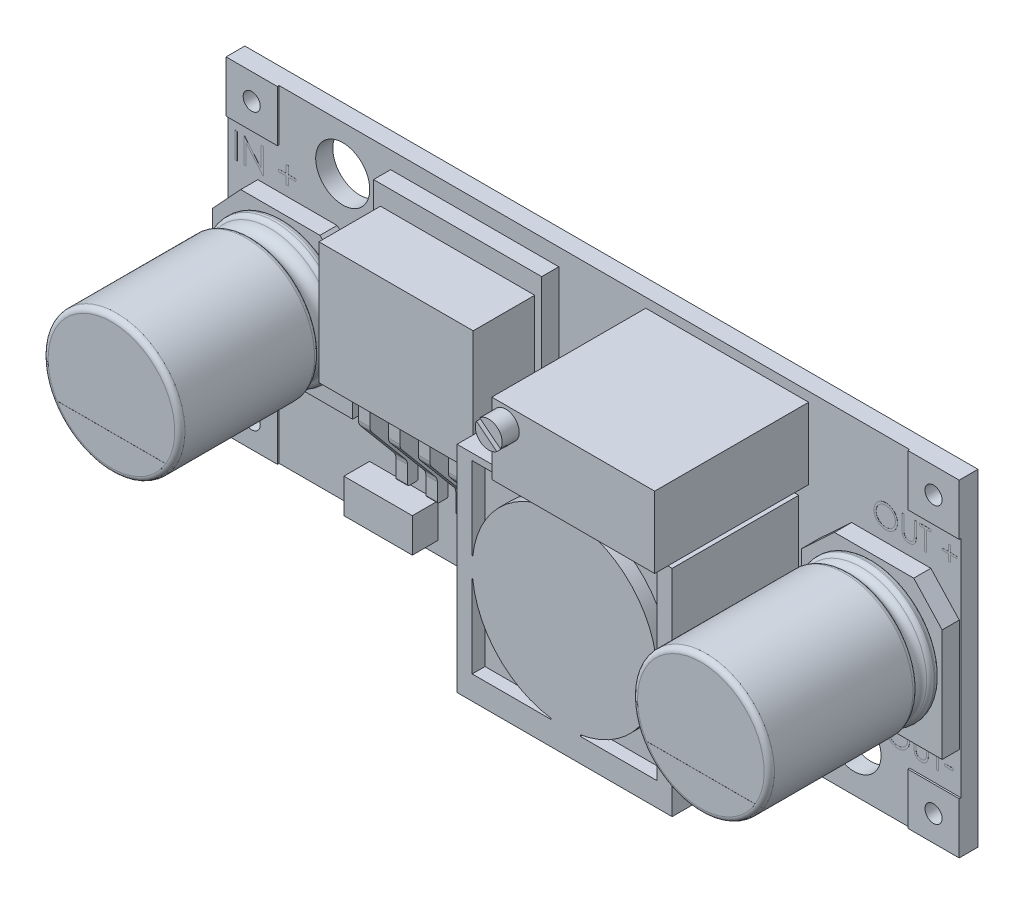
SolidWorks part; units mm, degrees
ref_plane "Front Plane" through (0, 0, 0) normal (0, 0, 1) x (1, 0, 0)
ref_plane "Top Plane" through (0, 0, 0) normal (0, 1, 0) x (1, 0, 0)
ref_plane "Right Plane" through (0, 0, 0) normal (1, 0, 0) x (0, 0, -1)
sketch "Sketch1" plane through (0, 0, 0) normal (0, 0, 1) x (1, 0, 0)
  line L1 (21.4264, -9.5637) -> (-21.4264, -9.5637)
  line L2 (21.4264, -9.5637) -> (21.4264, 9.5637)
  line L3 (21.4264, 9.5637) -> (-21.4264, 9.5637)
  line L4 (-21.4264, -9.5637) -> (-21.4264, 9.5637)
  line L5 (21.4264, -9.5637) -> (-21.4264, 9.5637) construction
  line L6 (21.4264, 9.5637) -> (-21.4264, -9.5637) construction
  circle A0 centre (-14.7064, 6.9537) radius 1.58
  circle A1 centre (15.1764, -6.774) radius 1.58
  point P0 (0, 0)
extrude "Boss-Extrude1" add sketch "Sketch1" along normal blind 1
sketch "Sketch2" plane through (0, 0, 1) normal (0, 0, 1) x (1, 0, 0)
  line L1 (-21.4264, 9.5637) -> (-18.4264, 9.5637)
  line L2 (-21.4264, 9.5637) -> (-21.4264, 6.5637)
  line L3 (-21.4264, 6.5637) -> (-18.4264, 6.5637)
  line L4 (-18.4264, 9.5637) -> (-18.4264, 6.5637)
  line L8 (-18.4264, -9.5637) -> (-18.4264, -6.5637)
  line L9 (-21.4264, -6.5637) -> (-18.4264, -6.5637)
  line L10 (-21.4264, -9.5637) -> (-21.4264, -6.5637)
  line L11 (-21.4264, -9.5637) -> (-18.4264, -9.5637)
  line L12 (21.4264, -9.5637) -> (18.4264, -9.5637)
  line L13 (21.4264, -9.5637) -> (21.4264, -6.5637)
  line L14 (21.4264, -6.5637) -> (18.4264, -6.5637)
  line L15 (18.4264, -9.5637) -> (18.4264, -6.5637)
  line L16 (18.4264, 9.5637) -> (18.4264, 6.5637)
  line L17 (21.4264, 6.5637) -> (18.4264, 6.5637)
  line L18 (21.4264, 9.5637) -> (21.4264, 6.5637)
  line L19 (21.4264, 9.5637) -> (18.4264, 9.5637)
extrude "Boss-Extrude2" add sketch "Sketch2" along normal blind 0.1
sketch "Sketch3" plane through (0, 0, 1.1) normal (0, 0, 1) x (1, 0, 0)
  circle A0 centre (-19.9264, 8.0637) radius 0.5
  circle A1 centre (-19.9264, -8.0637) radius 0.5
  circle A2 centre (19.9264, -8.0637) radius 0.5
  circle A3 centre (19.9264, 8.0637) radius 0.5
extrude "Cut-Extrude1" cut sketch "Sketch3" against normal blind 5
sketch "Sketch4" plane through (0, 0, 1) normal (0, 0, 1) x (1, 0, 0)
  line L5 (-21.3314, 2.3832) -> (-19.6699, 4.175)
  line L6 (-19.6699, 4.175) -> (-15.0378, 4.175)
  line L7 (-21.3314, -4.175) -> (-13.1214, -4.175)
  line L8 (-21.3314, -4.175) -> (-21.3314, 2.3832)
  line L9 (-19.6699, 4.175) -> (-15.0378, 4.175)
  line L10 (-13.1214, -4.175) -> (-13.1214, 2.398)
  line L11 (-21.3314, -4.175) -> (-14.0353, 3.2455) construction
  line L12 (-20.4763, 3.3054) -> (-13.1214, -4.175) construction
  line L13 (-15.0378, 4.175) -> (-13.1214, 2.398)
  line L14 (20.4763, 3.3054) -> (13.1214, -4.175) construction
  line L15 (21.3314, -4.175) -> (14.0353, 3.2455) construction
  line L16 (15.0378, 4.175) -> (13.1214, 2.398)
  line L17 (13.1214, -4.175) -> (13.1214, 2.398)
  line L18 (19.6699, 4.175) -> (15.0378, 4.175)
  line L19 (21.3314, -4.175) -> (21.3314, 2.3832)
  line L20 (21.3314, -4.175) -> (13.1214, -4.175)
  line L21 (19.6699, 4.175) -> (15.0378, 4.175)
  line L22 (21.3314, 2.3832) -> (19.6699, 4.175)
  point P13 (-17.2264, 0)
  point P28 (17.2264, 0)
extrude "Boss-Extrude3" add sketch "Sketch4" along normal blind 1 contours L13 L6 L5 L8 L7 L10 | L19 L22 L18 L16 L17 L20
sketch "Sketch5" plane through (0, 0, 2) normal (0, 0, 1) x (1, 0, 0)
  circle A0 centre (-17.2264, 0) radius 4.105
  circle A1 centre (17.2264, 0) radius 4.105
sketch "Sketch6" plane through (0, 0, 1) normal (0, 0, 1) x (1, 0, 0)
  line L5 (-11.9064, 8.5637) -> (-2.0764, 8.5637)
  line L6 (-11.9064, 8.5637) -> (-11.9064, -0.1863)
  line L7 (-11.9064, -0.1863) -> (-2.0764, -0.1863)
  line L8 (-2.0764, 8.5637) -> (-2.0764, -0.1863)
extrude "Boss-Extrude5" add sketch "Sketch6" along normal blind 4.6
sketch "Sketch7" plane through (0, 0, 5.6) normal (0, 0, 1) x (1, 0, 0)
  line L3 (-11.4988, 7.4182) -> (-2.4839, 7.4182)
  line L4 (-11.4988, 0.2879) -> (-2.4839, 0.2879)
  line L5 (-11.4988, 0.2879) -> (-11.4988, 7.4182)
  line L7 (-2.4839, 0.2879) -> (-2.4839, 7.4182)
  line L11 (-11.9064, -0.1863) -> (-2.0764, -0.1863)
  line L12 (-11.9064, -0.1863) -> (-11.9064, 8.5637)
  line L13 (-11.9064, 8.5637) -> (-2.0764, 8.5637)
  line L14 (-2.0764, -0.1863) -> (-2.0764, 8.5637)
  point P6 (-6.9914, 4.1887)
  point P13 (-6.9914, 4.1887)
extrude "Cut-Extrude2" cut sketch "Sketch7" against normal blind 3.6
sketch "Sketch8" plane through (0, 0.2879, 0) normal (0, -1, 0) x (-1, 0, 0)
  line L0 (9.1927, -4.7708) -> (9.1927, -1.0208)
  line L1 (10.9427, -4.7708) -> (10.2713, -4.7708)
  line L2 (10.9427, -4.7708) -> (10.9427, -1.0208)
  line L3 (10.9427, -1.0208) -> (10.2713, -1.0208)
  line L4 (10.2713, -4.7708) -> (10.2713, -1.0208)
  line L5 (9.1927, -4.7708) -> (8.5213, -4.7708)
  line L6 (8.5213, -4.7708) -> (8.5213, -1.0208)
  line L7 (9.1927, -1.0208) -> (8.5213, -1.0208)
  line L8 (7.4427, -4.7708) -> (7.4427, -1.0208)
  line L9 (7.4427, -4.7708) -> (6.7713, -4.7708)
  line L10 (6.7713, -4.7708) -> (6.7713, -1.0208)
  line L11 (7.4427, -1.0208) -> (6.7713, -1.0208)
  line L12 (5.6927, -4.7708) -> (5.6927, -1.0208)
  line L13 (5.6927, -4.7708) -> (5.0213, -4.7708)
  line L14 (5.0213, -4.7708) -> (5.0213, -1.0208)
  line L15 (5.6927, -1.0208) -> (5.0213, -1.0208)
  line L16 (3.9427, -4.7708) -> (3.9427, -1.0208)
  line L17 (3.9427, -4.7708) -> (3.2713, -4.7708)
  line L18 (3.2713, -4.7708) -> (3.2713, -1.0208)
  line L19 (3.9427, -1.0208) -> (3.2713, -1.0208)
  dimension "D1" = 5
extrude "Boss-Extrude6" add sketch "Sketch8" along normal blind 8
sketch "Sketch10" plane through (0, 0, 1) normal (0, 0, 1) x (1, 0, 0)
  line L5 (11.9464, -8.5637) -> (-0.6236, -8.5637)
  line L6 (11.9464, -8.5637) -> (11.9464, 4.0063)
  line L7 (11.9464, 4.0063) -> (-0.6236, 4.0063)
  line L8 (-0.6236, -8.5637) -> (-0.6236, 4.0063)
extrude "Boss-Extrude7" add sketch "Sketch10" along normal blind 7.4
sketch "Sketch11" plane through (0, 0, 8.4) normal (0, 0, 1) x (1, 0, 0)
  line L0 (0.2614, -1.1682) -> (0.2922, -1.2029)
  line L3 (0.2614, -2.3394) -> (0.2922, -2.3545)
  line L4 (0.2614, -7.1787) -> (4.8799, -7.1787)
  line L5 (0.2614, -7.1787) -> (0.2614, -2.3394)
  line L6 (0.2614, 3.6213) -> (4.9528, 3.6213)
  line L7 (11.0614, -7.1787) -> (11.0614, -2.7691)
  line L8 (0.2614, -7.1787) -> (11.0614, 3.6213) construction
  line L9 (0.2614, 3.6213) -> (11.0614, -7.1787) construction
  line L10 (4.9528, 3.6213) -> (4.9528, 3.5746)
  line L11 (6.2806, 3.6213) -> (6.2806, 3.5857)
  line L12 (10.9698, -0.7882) -> (11.0614, -0.7882)
  line L13 (10.9698, -2.7691) -> (11.0614, -2.7691)
  line L14 (4.8799, -7.1787) -> (4.8799, -7.1218)
  line L15 (6.582, -7.1787) -> (6.582, -7.0996)
  line L16 (6.582, -7.1787) -> (11.0614, -7.1787)
  line L17 (0.2614, -1.1682) -> (0.2614, 3.6213)
  line L18 (6.2806, 3.6213) -> (11.0614, 3.6213)
  line L19 (11.0614, -0.7882) -> (11.0614, 3.6213)
  arc A0 (6.582, -7.0996) -> (10.9698, -2.7691) centre (5.6614, -1.7787) ccw
  arc A1 (0.2922, -2.3545) -> (4.8799, -7.1218) centre (5.6614, -1.7787) ccw
  arc A2 (4.9528, 3.5746) -> (0.2922, -1.2029) centre (5.6614, -1.7787) ccw
  arc A3 (10.9698, -0.7882) -> (6.2806, 3.5857) centre (5.6614, -1.7787) ccw
  point P6 (5.6614, -1.7787)
extrude "Cut-Extrude7" cut sketch "Sketch11" against normal blind 0.75
sketch "Sketch13" plane through (0, 0, 1) normal (0, 0, 1) x (1, 0, 0)
  line L1 (12.527, 4.8371) -> (3.007, 4.8371)
  line L2 (12.527, 4.8371) -> (12.527, 9.0071)
  line L3 (12.527, 9.0071) -> (3.007, 9.0071)
  line L4 (3.007, 4.8371) -> (3.007, 9.0071)
extrude "Boss-Extrude8" add sketch "Sketch13" along normal blind 9
sketch "Sketch14" plane through (0, 0, 10) normal (0, 0, 1) x (1, 0, 0)
  circle A0 centre (3.8265, 8.0224) radius 0.7858
extrude "Boss-Extrude9" add sketch "Sketch14" along normal blind 1
sketch "Sketch16" plane through (0, 0, 11) normal (0, 0, 1) x (1, 0, 0)
  line L0 (3.1748, 8.7082) -> (4.6558, 7.5307)
  line L1 (4.6558, 7.5307) -> (4.4523, 7.2747)
  line L2 (4.4523, 7.2747) -> (2.9713, 8.4522)
  line L3 (2.9713, 8.4522) -> (3.1748, 8.7082)
extrude "Cut-Extrude8" cut sketch "Sketch16" against normal blind 0.4
sketch "Sketch17" plane through (0, 0, 0) normal (0, 1, 0) x (1, 0, 0)
  line L0 (-17.2264, -2) -> (-17.2264, -12)
  line L1 (-21.3314, -2) -> (-13.1214, -2) construction
  line L2 (-17.2264, -12) -> (-20.9264, -12)
  line L3 (-21.2264, -11.7) -> (-21.2264, -4.1269)
  line L4 (-20.9264, -2) -> (-17.2264, -2)
  line L5 (-21.2264, -2.4494) -> (-21.2264, -2.3)
  arc A0 (-21.0274, -2.7319) -> (-21.0274, -3.8444) centre (-21.2264, -3.2881) cw
  arc A1 (-20.9264, -2) -> (-21.2264, -2.3) centre (-20.9264, -2.3) ccw
  arc A2 (-21.2264, -2.4494) -> (-21.0274, -2.7319) centre (-20.9264, -2.4494) ccw
  arc A3 (-21.0274, -3.8444) -> (-21.2264, -4.1269) centre (-20.9264, -4.1269) ccw
  arc A4 (-21.2264, -11.7) -> (-20.9264, -12) centre (-20.9264, -11.7) ccw
  point P12 (-21.2264, -2)
  point P15 (-21.2264, -2.6973)
  point P20 (-21.2264, -12)
  dimension "D3" = 0.3
  dimension "D4" = 0.3
  dimension "D5" = 0.3
  dimension "D6" = 0.3
  dimension "D1" = 10
  dimension "D2" = 4
revolve "Revolve1" add sketch "Sketch17" angle 360 about L0
sketch "Sketch18" plane through (0, 0, 0) normal (0, 1, 0) x (1, 0, 0)
  line L0 (17.2264, -2) -> (17.2264, -12)
  line L1 (21.3314, -2) -> (13.1214, -2) construction
  line L2 (17.2264, -12) -> (20.9264, -12)
  line L3 (21.2264, -11.7) -> (21.2264, -3.6026)
  line L4 (20.9264, -2) -> (17.2264, -2)
  line L5 (21.2264, -2.364) -> (21.2264, -2.3)
  arc A0 (21.0572, -2.634) -> (21.0572, -3.3326) centre (21.2264, -2.9833) ccw
  arc A1 (21.2264, -11.7) -> (20.9264, -12) centre (20.9264, -11.7) cw
  arc A2 (21.0572, -3.3326) -> (21.2264, -3.6026) centre (20.9264, -3.6026) cw
  arc A3 (21.0572, -2.634) -> (21.2264, -2.364) centre (20.9264, -2.364) ccw
  arc A4 (20.9264, -2) -> (21.2264, -2.3) centre (20.9264, -2.3) cw
  point P11 (21.2264, -12)
  point P16 (21.2264, -2.5952)
  point P19 (21.2264, -2)
  dimension "D3" = 0.3
  dimension "D1" = 10
  dimension "D2" = 4
revolve "Revolve2" add sketch "Sketch18" angle 360 about L0
sketch "Sketch20" plane through (-10.9427, 0, 0) normal (-1, 0, 0) x (0, 0, 1)
  line L0 (3.8444, 0.2896) -> (3.8444, -2.2336)
  line L1 (3.8444, 3.801) -> (3.8444, -3.801) construction
  line L2 (3.7275, -2.5549) -> (1.7713, -4.8877)
  line L3 (1.6544, -5.209) -> (1.6544, -6.2296)
  line L4 (1.5544, -6.3296) -> (1.1197, -6.3296)
  line L5 (1.0208, -7.7121) -> (1.0208, -0.1863) construction
  line L6 (1.0197, -6.2308) -> (1.0208, -4.4558)
  line L8 (1.1189, -4.3365) -> (2.9146, -2.1951)
  line L9 (8.1377, -10.4913) -> (1.0208, -10.4913)
  line L10 (3.0315, 0.2896) -> (3.0315, -1.8738)
  line L11 (1.0208, -4.4558) -> (1.1189, -4.3365)
  line L12 (3.0315, 0.2896) -> (1, 0.2896)
  line L13 (8.1377, -10.4913) -> (8.1377, 0.2896)
  line L14 (8.1377, 0.2896) -> (3.8444, 0.2896)
  line L15 (1, 6.5637) -> (1, -6.5637) construction
  line L16 (1, 0.2896) -> (1.0208, -10.4913)
  arc A1 (1.6544, -5.209) -> (1.7713, -4.8877) centre (2.1544, -5.209) cw
  arc A2 (2.9146, -2.1951) -> (3.0315, -1.8738) centre (2.5315, -1.8738) ccw
  arc A3 (3.8444, -2.2336) -> (3.7275, -2.5549) centre (3.3444, -2.2336) cw
  arc A4 (1.1197, -6.3296) -> (1.0197, -6.2308) centre (1.1197, -6.2296) cw
  arc A5 (1.5544, -6.3296) -> (1.6544, -6.2296) centre (1.5544, -6.2296) ccw
  point P23 (3.8444, -2.4155)
  point P26 (1.0208, -6.3296)
  dimension "D2" = 0.1
extrude "Cut-Extrude10" cut sketch "Sketch20" against normal blind 9
sketch "Sketch21" plane through (-10.9427, 0, 0) normal (1, 0, 0) x (0, 0, -1)
  line L0 (-2, -0.1841) -> (-1, -0.1841)
  line L1 (-2, -4.175) -> (-2, 2.3832) construction
  line L2 (-1, -4.175) -> (-1, 2.3832) construction
  line L3 (-2, -0.1841) -> (-2, 0.2879)
  line L4 (-1, -0.1841) -> (-1, 0.2879)
  line L5 (-1, 0.2879) -> (-2, 0.2879)
extrude "Boss-Extrude11" add sketch "Sketch21" along normal blind 8.8665
sketch "Sketch24" plane through (0, 0, 0) normal (0, 0, -1) x (-1, 0, 0)
  text T0 "<b>DC to DC</b>"
extrude "Boss-Extrude15" add sketch "Sketch24" along normal blind 0.005
sketch "Sketch25" plane through (0, 0, 12) normal (0, 0, 1) x (1, 0, 0)
  line L0 (-20.4073, -1.8899) -> (-14.0455, -1.8899)
  line L1 (14.0455, -1.8899) -> (20.4073, -1.8899)
  circle A0 centre (-17.2264, 0) radius 3.7 construction
  arc A1 (-20.4073, -1.8899) -> (-14.0455, -1.8899) centre (-17.2264, 0) ccw
  circle A2 centre (17.2264, 0) radius 3.7 construction
  arc A3 (14.0455, -1.8899) -> (20.4073, -1.8899) centre (17.2264, 0) ccw
extrude "Boss-Extrude16" add sketch "Sketch25" along normal blind 0.005
sketch "Sketch26" plane through (0, 0, 1) normal (0, 0, 1) x (1, 0, 0)
  line L0 (-9.1386, -6.8179) -> (-13.1386, -6.8179)
  line L1 (-9.1386, -6.8179) -> (-9.1386, -8.8179)
  line L2 (-9.1386, -8.8179) -> (-13.1386, -8.8179)
  line L3 (-13.1386, -8.8179) -> (-13.1386, -6.8179)
  dimension "D1" = 2
  dimension "D2" = 4
extrude "Boss-Extrude18" add sketch "Sketch26" along normal blind 1.5
sketch "Sketch28" plane through (0, 0, 1) normal (0, 0, 1) x (1, 0, 0)
  text T0 "IN-" font "Century Gothic" height 1.5
extrude "Boss-Extrude19" add sketch "Sketch28" along normal blind 0.005
sketch "Sketch29" plane through (0, 0, 1) normal (0, 0, 1) x (1, 0, 0)
  text T0 "IN +" font "Century Gothic" height 1.5
extrude "Boss-Extrude20" add sketch "Sketch29" along normal blind 0.005
sketch "Sketch30" plane through (0, 0, 1) normal (0, 0, 1) x (1, 0, 0)
  text T0 "OUT +" font "Century Gothic" height 1.3
extrude "Boss-Extrude21" add sketch "Sketch30" along normal blind 0.005
sketch "Sketch32" plane through (0, 0, 1) normal (0, 0, 1) x (1, 0, 0)
  text T0 "OUT-" font "Century Gothic" height 1.3
extrude "Boss-Extrude23" add sketch "Sketch32" along normal blind 0.005
